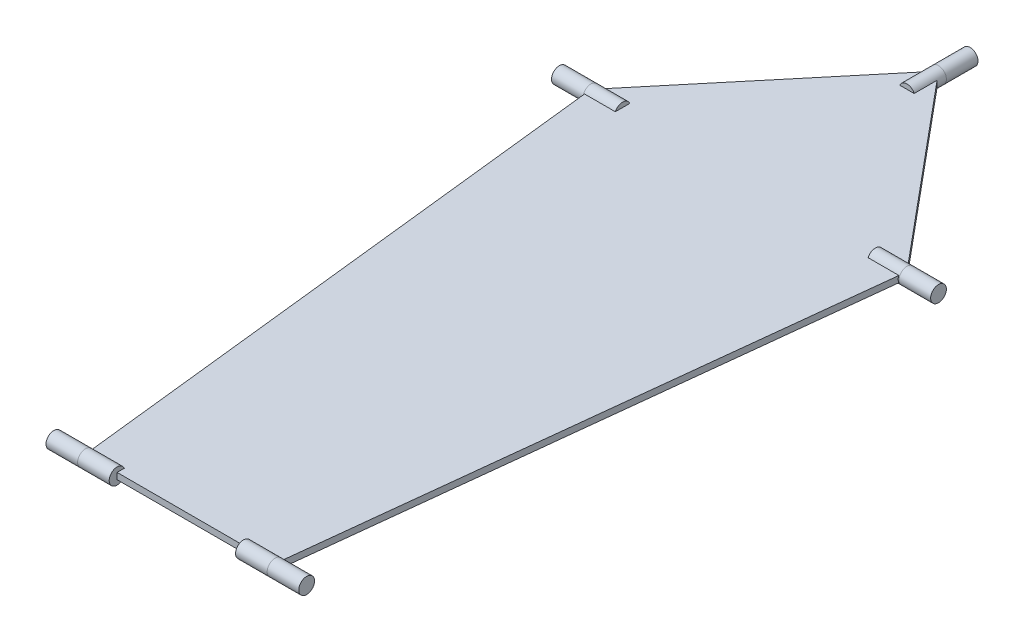
SolidWorks part; units mm, degrees
ref_plane "Front Plane" through (0, 0, 0) normal (0, 0, 1) x (1, 0, 0)
ref_plane "Top Plane" through (0, 0, 0) normal (0, 1, 0) x (1, 0, 0)
ref_plane "Right Plane" through (0, 0, 0) normal (1, 0, 0) x (0, 0, -1)
sketch "Sketch1" plane through (0, 0, 0) normal (0, 1, 0) x (1, 0, 0)
  line L0 (0, 152.4) -> (0, -152.4)
  line L1 (0, -152.4) -> (-38.1, -152.4)
  line L2 (-38.1, -152.4) -> (-63.5, 76.2)
  line L3 (-63.5, 76.2) -> (0, 152.4)
  point P4 (0, 0)
  point P7 (-13.1075, -45.7914)
  point P8 (-23.8545, 21.0683)
  dimension "D1" = 38.1
  dimension "D2" = 63.5
  dimension "D3" = 76.2
  dimension "D4" = 228.6
extrude "Boss-Extrude1" add sketch "Sketch1" along normal mid plane 2.54
mirror "Mirror1" about plane through (0, 0, 0) normal (1, 0, 0) of "Boss-Extrude1"
sketch "Sketch2" plane through (0, 0, 0) normal (0, 1, 0) x (1, 0, 0)
  line L0 (-63.5, 76.2) -> (-50.8, 76.2)
  line L3 (-63.5, 76.2) -> (-76.2, 76.2)
  dimension "D1" = 12.7
sweep "Sweep1" add path "Sketch2" circular profile diameter 6.35 parameters "D3"=6.35
sketch "Sketch10" plane through (0, 0, 0) normal (0, 1, 0) x (1, 0, 0)
  line L1 (-63.1767, 73.2901) -> (-38.1, -152.4) construction
  line L2 (-38.1, -152.4) -> (-50.8, -152.4)
  line L3 (-63.1767, 73.2901) -> (-38.1, -152.4) construction
  line L4 (-38.1, -152.4) -> (-25.4, -152.4)
  dimension "D1" = 12.7
sweep "Sweep2" add path "Sketch10" circular profile diameter 6.35 parameters "D3"=6.35
mirror "Mirror3" about plane through (0, 0, 0) normal (1, 0, 0) of "Sweep2", "Sweep1"
sketch "Sketch36" plane through (0, 0, 0) normal (0, 1, 0) x (1, 0, 0)
  line L0 (0, 152.4) -> (0, 165.1)
  line L1 (0, 152.4) -> (0, 139.7)
  dimension "D1" = 12.7
sweep "Sweep3" add path "Sketch36" circular profile diameter 6.35 parameters "D3"=6.35
equation "\"HipWidth\" = 3"
equation "\"D1@Sketch1\"=\"HipWidth\"/2"
equation "\"ShoulderWidth\" = 5"
equation "\"D2@Sketch1\"=\"ShoulderWidth\"/2"
equation "\"ShoulderNeckDist\" = 3"
equation "\"D3@Sketch1\"=\"ShoulderNeckDist\""
equation "\"ShoulderHipDist\"= 9"
equation "\"D4@Sketch1\"=\"ShoulderHipDist\""
equation "\"stickout\"=0.5"
equation "\"D1@Sketch2\"=\"stickout\""
equation "\"D1@Sketch10\"=\"stickout\""
equation "\"D1@Sketch36\"=\"stickout\""
